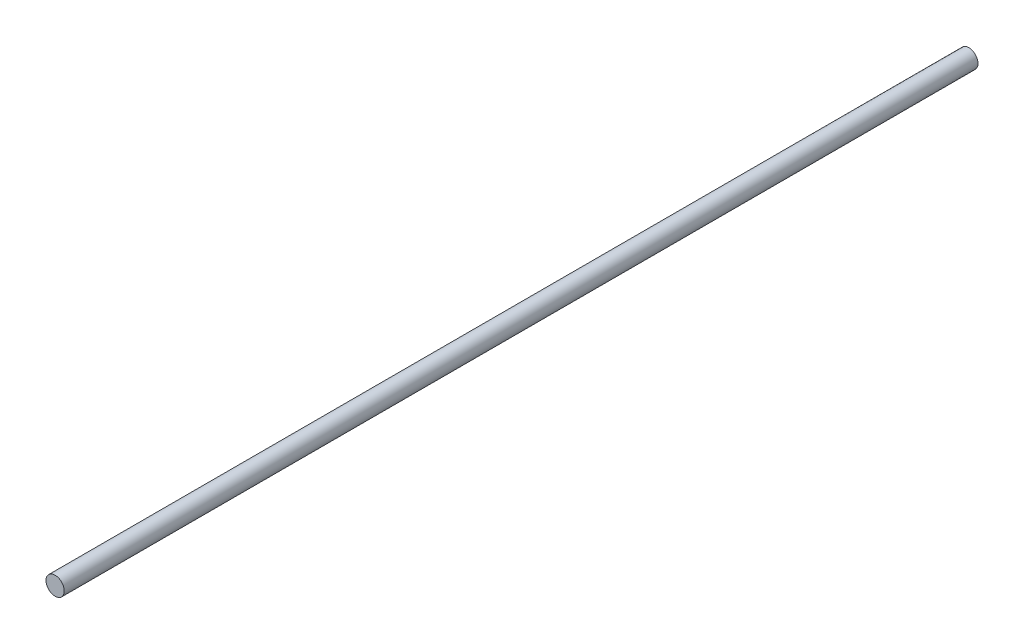
SolidWorks part; units mm, degrees
ref_plane "Спереди" through (0, 0, 0) normal (0, 0, 1) x (1, 0, 0)
ref_plane "Сверху" through (0, 0, 0) normal (0, 1, 0) x (1, 0, 0)
ref_plane "Справа" through (0, 0, 0) normal (1, 0, 0) x (0, 0, -1)
sketch "Эскиз1" plane through (0, 0, 0) normal (0, 0, 1) x (1, 0, 0)
  circle A0 centre (0, 0) radius 4
extrude "Бобышка-Вытянуть1" add sketch "Эскиз1" along normal blind 400
